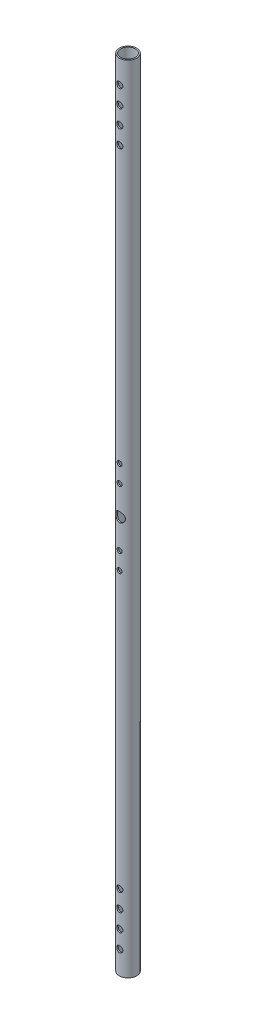
SolidWorks part; units mm, degrees
material "7075-T6 (SN)"
ref_plane "前视基准面" through (0, 0, 0) normal (0, 0, 1) x (1, 0, 0)
ref_plane "上视基准面" through (0, 0, 0) normal (0, 1, 0) x (1, 0, 0)
ref_plane "右视基准面" through (0, 0, 0) normal (1, 0, 0) x (0, 0, -1)
other "Configuration Table"
sketch "草图1" plane through (0, 0, 0) normal (0, 1, 0) x (1, 0, 0)
  circle A0 centre (0, 0) radius 7.5
  circle A1 centre (0, 0) radius 6.375
  dimension "D1" = 15
  dimension "D2" = 12.75
extrude "凸台-拉伸1" add sketch "草图1" along normal blind 685
sketch "草图2" plane through (12.5, 0, 0) normal (0, 0, 1) x (1, 0, 0)
  circle A8 centre (-12.5, 20) radius 2.65 construction
  circle A9 centre (-12.5, 35) radius 2.65 construction
  circle A10 centre (-12.5, 50) radius 2.65 construction
  circle A11 centre (-12.5, 65) radius 2.65 construction
  circle A12 centre (-12.5, 20) radius 2.65
  circle A13 centre (-12.5, 35) radius 2.65
  circle A14 centre (-12.5, 50) radius 2.65
  circle A15 centre (-12.5, 65) radius 2.65
  circle A16 centre (-12.5, 302.5) radius 2.15 construction
  circle A17 centre (-12.5, 317.5) radius 2.15 construction
  circle A18 centre (-12.5, 342.5) radius 4.15 construction
  circle A19 centre (-12.5, 367.5) radius 2.15 construction
  circle A20 centre (-12.5, 382.5) radius 2.15 construction
  circle A21 centre (-12.5, 302.5) radius 2.15
  circle A22 centre (-12.5, 317.5) radius 2.15
  circle A23 centre (-12.5, 342.5) radius 4.15
  circle A24 centre (-12.5, 367.5) radius 2.15
  circle A25 centre (-12.5, 382.5) radius 2.15
extrude "切除-拉伸1" cut sketch "草图2" against normal through all both and the other way through all
ref_plane "基准面1" through (0, 342.5, 0) normal (0, 1, 0) x (1, 0, 0)
mirror "镜向1" about plane through (0, 342.5, 0) normal (0, 1, 0) of "切除-拉伸1"
